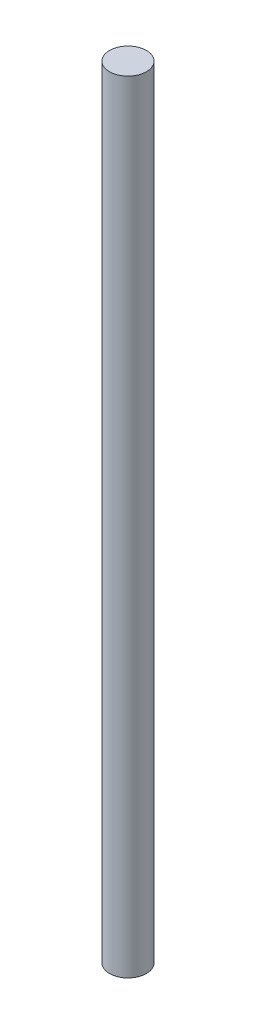
SolidWorks part; units mm, degrees
ref_plane "Front Plane" through (0, 0, 0) normal (0, 0, 1) x (1, 0, 0)
ref_plane "Top Plane" through (0, 0, 0) normal (0, 1, 0) x (1, 0, 0)
ref_plane "Right Plane" through (0, 0, 0) normal (1, 0, 0) x (0, 0, -1)
sketch "Sketch1" plane through (0, 0, 0) normal (0, 1, 0) x (1, 0, 0)
  circle A0 centre (0, 0) radius 6
extrude "Boss-Extrude1" add sketch "Sketch1" along normal blind 254
